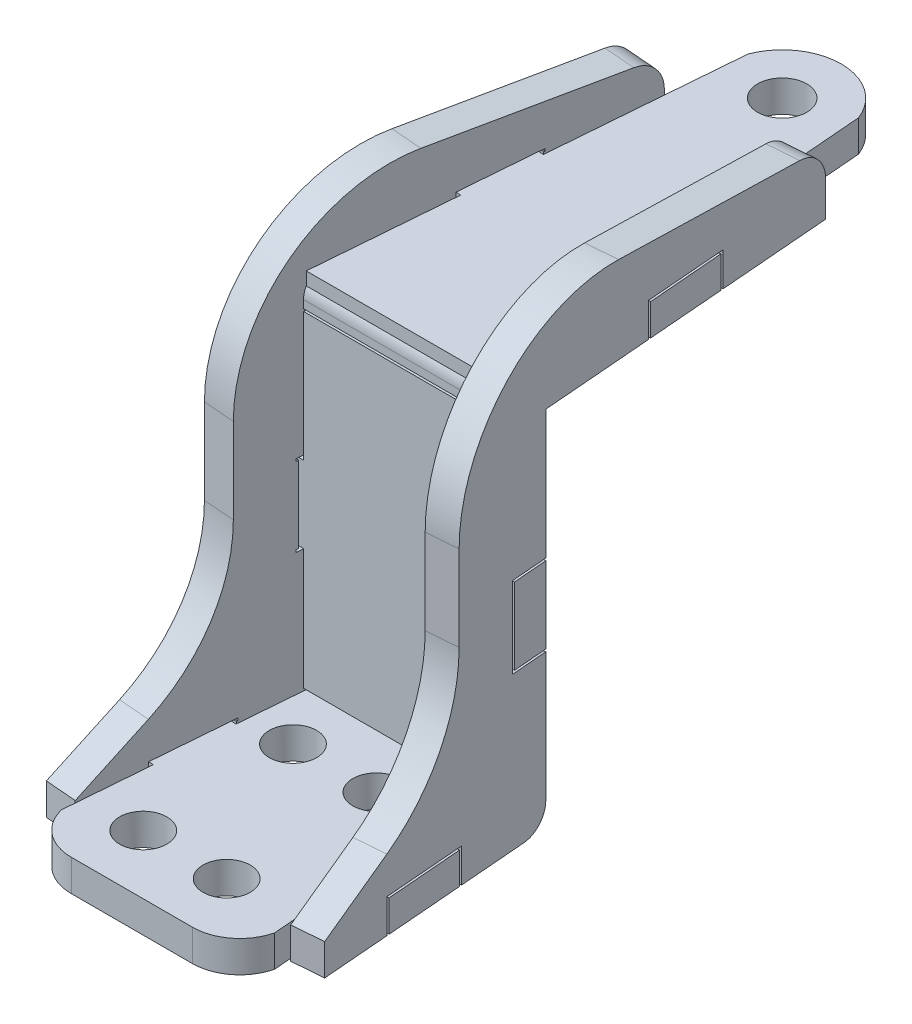
SolidWorks part; units mm, degrees
material "Plain Carbon Steel"
ref_plane "Front Plane" through (0, 0, 0) normal (0, 0, 1) x (1, 0, 0)
ref_plane "Top Plane" through (0, 0, 0) normal (0, 1, 0) x (1, 0, 0)
ref_plane "Right Plane" through (0, 0, 0) normal (1, 0, 0) x (0, 0, -1)
sketch "Sketch1" plane through (0, 0, 0) normal (1, 0, 0) x (0, 0, -1)
  line L0 (0, 0) -> (-54, 0)
  line L1 (-55, -1) -> (-55, -45)
  line L2 (-56, -46) -> (-90, -46)
  arc A0 (-55, -45) -> (-56, -46) centre (-56, -45) cw
  arc A1 (-54, 0) -> (-55, -1) centre (-54, -1) ccw
  point P7 (-55, -46)
  point P10 (-55, 0)
  dimension "D4" = 1
  dimension "D1" = 46
  dimension "D2" = 35
  dimension "D3" = 55
extrude "Extrude-Thin1" add sketch "Sketch1" along normal mid plane 30 thin
sketch "Sketch2" plane through (0, 2, 0) normal (0, 1, 0) x (1, 0, 0)
  line L0 (-15, -73.5) -> (15, -73.5) construction
  line L1 (15, -57) -> (15, -90) construction
  line L2 (-15, -57) -> (-15, -90) construction
  line L3 (15, -56) -> (-15, -56) construction
  line L6 (-6.0613, -82.5) -> (-6.0613, -63.5) construction
  line L7 (-6.0613, -63.5) -> (4.5257, -63.5) construction
  line L8 (4.5257, -63.5) -> (4.5257, -82.5) construction
  line L9 (4.5257, -82.5) -> (-6.0613, -82.5) construction
  line L13 (15, -90) -> (-15, -90) construction
  line L15 (0, -7.5) -> (0, 0) construction
  line L16 (15, 0) -> (-15, 0) construction
  line L17 (-7.4756, -6.8958) -> (-15, -100)
  line L18 (-15, 0) -> (-15, -54) construction
  line L19 (7.4756, -6.8958) -> (15, -100)
  line L20 (-15, -100) -> (-17.6002, 8.4483)
  line L21 (-17.6002, 8.4483) -> (38.4266, 9.4295)
  line L22 (38.4266, 9.4295) -> (15, -100)
  circle A0 centre (0, -7.5) radius 3.125
  arc A1 (7.4756, -6.8958) -> (-7.4756, -6.8958) centre (0, -7.5) ccw
  circle A3 centre (-6.0613, -82.5) radius 3
  circle A4 centre (-6.0613, -63.5) radius 3
  circle A5 centre (4.5257, -82.5) radius 3
  circle A6 centre (4.5257, -63.5) radius 3
  circle A7 centre (4.5257, -63.5) radius 7.5 construction
  circle A8 centre (-6.0613, -82.5) radius 7.5 construction
  dimension "D1" = 6.25
  dimension "D2" = 6
  dimension "D3" = 15
  dimension "D4" = 15
  dimension "D5" = 100
extrude "Cut-Extrude1" cut sketch "Sketch2" against normal through all
fillet "Fillet1" radius 6 2 edges at (14.1918, -46, 90) (-14.1918, -46, 90)
sketch "Sketch8" plane through (6.8734, 0, -0.5555) normal (0.9968, 0, -0.0806) x (-0.0806, 0, -0.9968)
  line L0 (-7.4756, 2) -> (0.0244, 2) construction
  line L3 (-53.7301, -45) -> (-53.7301, -2) construction
  line L4 (-53.7301, -2) -> (-7.4756, -2) construction
  line L5 (-56.7399, -48) -> (-84.3463, -48)
  line L6 (-53.7301, -45) -> (-53.7301, -2)
  line L7 (-53.7301, -2) -> (-14.9756, -2)
  line L8 (-14.9756, 2) -> (-14.9756, -2)
  line L9 (-7.4756, 2) -> (-14.9756, 2) construction
  line L10 (-7.4756, 2) -> (-54.7334, 2) construction
  line L11 (-14.9756, 2) -> (-14.9756, 2.3977)
  line L12 (-18.5583, 6.3759) -> (-43.6433, 9.0076)
  line L13 (-65.7301, -10.8832) -> (-65.7301, -21.7049)
  line L14 (-75.7301, -39.0255) -> (-84.3463, -44)
  line L15 (-84.3463, -44) -> (-84.3463, -48)
  arc A0 (-65.7301, -21.7049) -> (-75.7301, -39.0255) centre (-85.7301, -21.7049) cw
  arc A1 (-43.6433, 9.0076) -> (-65.7301, -10.8832) centre (-45.7301, -10.8832) ccw
  arc A2 (-14.9756, 2.3977) -> (-18.5583, 6.3759) centre (-18.9756, 2.3977) ccw
  ellipse E1 centre (-56.7399, -45) end of major axis (-53.7301, -45) minor radius 3 (-56.7399, -48) -> (-53.7301, -45) ccw construction
  ellipse E3 centre (-56.7399, -45) end of major axis (-53.7301, -45) minor radius 3 (-56.7399, -48) -> (-53.7301, -45) ccw
  point P46 (-14.9756, 6)
  dimension "D3" = 20
  dimension "D6" = 4
  dimension "D1" = 4
  dimension "D2" = 12
  dimension "D4" = 12
  dimension "D5" = 30
extrude "Boss-Extrude1" add sketch "Sketch8" along normal blind 4
mirror "Mirror1" about plane through (0, 0, 0) normal (1, 0, 0) of "Boss-Extrude1"
sketch "Sketch9" plane through (0, 0, 0) normal (1, 0, 0) x (0, 0, -1)
  line L0 (-28.3635, 2.15) -> (-38.3635, 2.15)
  line L1 (-52.6778, -2) -> (-14.0493, -2) construction
  line L2 (-57.15, -18.5) -> (-57.15, -28.5)
  line L3 (-52.6778, -45) -> (-52.6778, -2) construction
  line L4 (-64.4361, -43.85) -> (-74.4361, -43.85)
  line L5 (-83.1945, -48) -> (-55.6778, -48) construction
  line L6 (-33.3635, 2.15) -> (-33.3635, -2) construction
  line L7 (-57.15, -23.5) -> (-52.6778, -23.5) construction
  line L8 (-69.4361, -48) -> (-69.4361, -43.85) construction
  line L9 (-57, -44) -> (-57, -1) construction
  dimension "D1" = 4.15
  dimension "D2" = 0.15
  dimension "D3" = 4.15
  dimension "D4" = 10
extrude "Cut-Extrude-Thin1" cut sketch "Sketch9" against normal through all and the other way through all thin thin type mid plane wall 0.3
sketch "Sketch10" plane through (-10.8604, 0, -0.8777) normal (-0.9968, 0, -0.0806) x (-0.0806, 0, 0.9968)
  line L0 (29.3366, 2.3) -> (29.3366, -4.3414)
  line L2 (39.3692, -4.3898) -> (39.3692, 2.3)
  line L3 (65.5268, -43.7) -> (65.5268, -49.9329)
  line L4 (50.8913, -18.5) -> (58.3674, -18.5)
  line L6 (58.3674, -28.5) -> (46.5308, -28.5)
  line L7 (75.5594, -49.9336) -> (75.5594, -43.7)
extrude "Cut-Extrude-Thin2" cut sketch "Sketch10" against normal blind 4.3 thin thin type mid plane wall 0.3
sketch "Sketch11" plane through (-6.5744, 0, -0.5313) normal (-0.9968, 0, -0.0806) x (-0.0806, 0, 0.9968)
  line L0 (29.4866, -2) -> (39.2192, -2) construction
  line L1 (39.2192, -2) -> (39.2192, 2) construction
  line L2 (39.2192, 2) -> (29.4866, 2) construction
  line L3 (29.4866, 2) -> (29.4866, -2) construction
  line L4 (53.7301, -28.35) -> (58.0664, -28.35) construction
  line L5 (58.0664, -28.35) -> (58.0664, -18.65) construction
  line L6 (58.0664, -18.65) -> (53.7301, -18.65) construction
  line L7 (53.7301, -18.65) -> (53.7301, -28.35) construction
  line L8 (65.6768, -48) -> (75.4094, -48) construction
  line L9 (75.4094, -48) -> (75.4094, -44) construction
  line L10 (75.4094, -44) -> (65.6768, -44) construction
  line L11 (65.6768, -44) -> (65.6768, -48) construction
  line L12 (29.4866, -2) -> (39.2192, -2)
  line L13 (39.2192, -2) -> (39.2192, 2)
  line L14 (39.2192, 2) -> (29.4866, 2)
  line L15 (29.4866, 2) -> (29.4866, -2)
  line L16 (53.7301, -28.35) -> (58.0664, -28.35)
  line L17 (58.0664, -28.35) -> (58.0664, -18.65)
  line L18 (58.0664, -18.65) -> (53.7301, -18.65)
  line L19 (53.7301, -18.65) -> (53.7301, -28.35)
  line L20 (65.6768, -48) -> (75.4094, -48)
  line L21 (75.4094, -48) -> (75.4094, -44)
  line L22 (75.4094, -44) -> (65.6768, -44)
  line L23 (65.6768, -44) -> (65.6768, -48)
  circle A0 centre (49.1645, -12.4866) radius 56.7012
extrude "Cut-Extrude2" cut sketch "Sketch11" along normal blind 0.3
mirror "Mirror2" about plane through (0, 0, 0) normal (1, 0, 0) of "Cut-Extrude-Thin2"
mirror "Mirror3" about plane through (0, 0, 0) normal (1, 0, 0) of "Cut-Extrude2"
sketch "Sketch12" plane through (0, 0, 0) normal (1, 0, 0) x (0, 0, -1)
  line L0 (-53, -2) -> (-53, -45) construction
  line L1 (-52.6778, -2) -> (-56.6778, -2)
  line L2 (-52.6778, -2) -> (-52.6778, 2)
  line L3 (-52.6778, 2) -> (-56.6778, 2)
  line L4 (-56.6778, -2) -> (-56.6778, 2)
  line L5 (-57, -44) -> (-53, -44)
  line L6 (-57, -44) -> (-57, -48)
  line L7 (-57, -48) -> (-53, -48)
  line L8 (-53, -44) -> (-53, -48)
extrude "Boss-Extrude2" add sketch "Sketch12" against normal up to surface and the other way up to surface
sketch "Sketch14" plane through (0, -44, 0) normal (0, 1, 0) x (1, 0, 0)
  line L0 (-6.4862, -72.8775) -> (-16.8959, -72.5537)
  line L1 (-6.4862, -72.8775) -> (-6.5494, -74.9094)
  line L2 (-16.8959, -72.5537) -> (-16.9591, -74.5856)
  line L3 (-6.5494, -74.9094) -> (-16.9591, -74.5856)
  line L4 (-6.4862, -72.8775) -> (-16.9591, -74.5856) construction
  line L5 (-16.8959, -72.5537) -> (-6.5494, -74.9094) construction
  line L6 (0, -90) -> (0, -76.5882) construction
  line L7 (7.6874, -90) -> (-7.6874, -90) construction
  line L8 (16.8959, -72.5537) -> (6.5494, -74.9094) construction
  line L9 (6.4862, -72.8775) -> (16.9591, -74.5856) construction
  line L10 (6.5494, -74.9094) -> (16.9591, -74.5856)
  line L11 (16.8959, -72.5537) -> (16.9591, -74.5856)
  line L12 (6.4862, -72.8775) -> (6.5494, -74.9094)
  line L13 (6.4862, -72.8775) -> (16.8959, -72.5537)
  point P1 (-11.7226, -73.7316)
  point P13 (11.7226, -73.7316)
extrude "Cut-Extrude3" cut sketch "Sketch14" along normal blind 0.3
sketch "Sketch15" plane through (0, 2, 0) normal (0, 1, 0) x (1, 0, 0)
  line L0 (14.263, -38.2999) -> (-15.9747, -38.0546)
  line L1 (-15.9747, -38.0546) -> (0.9144, -39.9692)
  line L2 (0.9144, -39.9692) -> (14.263, -38.2999)
extrude "Cut-Extrude4" cut sketch "Sketch15" along normal blind 0.3
sketch "Sketch13" plane through (0, 0, 0) normal (1, 0, 0) x (0, 0, -1)
  line L0 (-49.7467, -43.85) -> (-75.8052, -43.85)
  line L2 (-79.9603, -2.15) -> (-43.9105, -2.15)
  line L4 (-38.5604, -2) -> (-53, -2) construction
  line L5 (-64.932, -44) -> (-57, -44) construction
  dimension "D1" = 0.15
  dimension "D2" = 0.15
extrude "Cut-Extrude-Thin3" cut sketch "Sketch13" against normal through all and the other way through all thin thin type mid plane wall 0.3
other "Save Bodies1"
